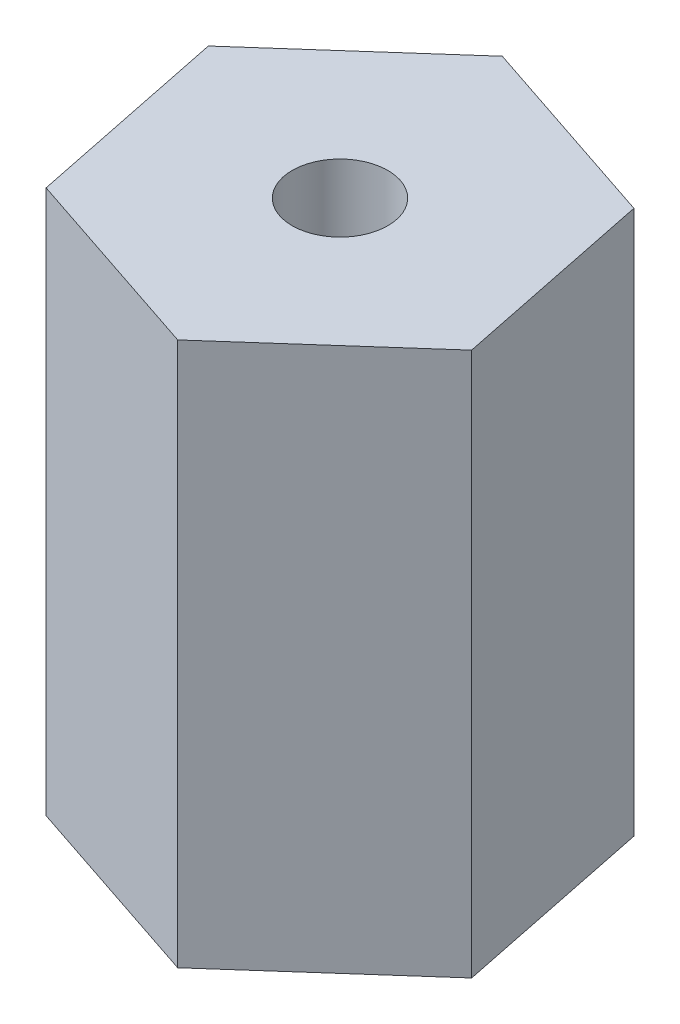
SolidWorks part; units mm, degrees
ref_plane "Front Plane" through (0, 0, 0) normal (0, 0, 1) x (1, 0, 0)
ref_plane "Top Plane" through (0, 0, 0) normal (0, 1, 0) x (1, 0, 0)
ref_plane "Right Plane" through (0, 0, 0) normal (1, 0, 0) x (0, 0, -1)
sketch "Sketch1" plane through (0, 0, 0) normal (0, 1, 0) x (1, 0, 0)
  line L1 (5.1581, 4.5716) -> (-1.3801, 6.7528)
  line L2 (-1.3801, 6.7528) -> (-6.5382, 2.1812)
  line L3 (-6.5382, 2.1812) -> (-5.1581, -4.5716)
  line L4 (-5.1581, -4.5716) -> (1.3801, -6.7528)
  line L5 (1.3801, -6.7528) -> (6.5382, -2.1812)
  line L6 (6.5382, -2.1812) -> (5.1581, 4.5716)
  circle A1 centre (0, 0) radius 5.969 construction
  dimension "D1" = 11.938
extrude "Boss-Extrude1" add sketch "Sketch1" along normal blind 18
sketch "Sketch2" plane through (0, 18, 0) normal (0, 1, 0) x (1, 0, 0)
  circle A0 centre (0, 0) radius 1.585
  dimension "D1" = 3.17
extrude "Cut-Extrude1" cut sketch "Sketch2" against normal through all
equation "\"MDF\"= 4.8mm"
equation "\"Foamcore\"= 4.6mm"
equation "\"PCB\" = 1.6mm"
equation "\"GMaterial\"= \"MDF\""
equation "\"BaseWidth\" = 10in"
equation "\"SkidLength\" = 1in"
equation "\"SkidClearance\" = 0.4in"
equation "\"MotorMountLength\" = 2in"
equation "\"MotorMountWidth\" = \"GMaterial\""
equation "\"MotorMountHeight\" = 2.25in"
equation "\"UnoStackWidth\" = 77.4mm"
equation "\"UnoStackLength\" = 79.8mm"
equation "\"UnoStackHeight\" = 34.2mm"
equation "\"TallHexRiserHeight\" = 22.2mm"
equation "\"PingPongBallSize\" = 40mm"
equation "\"BarrelLength\" = 9in"
equation "\"BarrelSize\" = \"PingPongBallSize\""
equation "\"PlatformLength\" = 4in"
equation "\"PlatformWidth\" = 6in"
equation "\"WheelWidth\"= 26mm"
equation "\"WheelDiameter\"=2.99213"
equation "\"ServoMountHeight\"=2.49223"
equation "\"ServoGearHeight\" = 0.95330261in"
equation "\"ServoMountLength\"= 1.53774"
equation "\"PivotHoleRadius\"= 0.616358"
equation "\"PlatformMountHeight\" = 3.19"
equation "\"TensionOffSet\"= .3mm"
equation "\"MotorMountWedge\"=0.333333"
equation "\"LaserCutterOffset\"= .3mm"
equation "\"BumperWidth\"=11"
equation "\"PitchingWheelBoltShoulder\" = 4.5mm"
equation "\"BrassCouplingLength\" = 18mm"
equation "\"PitcherWheelCompression\" = 2.5mm"
equation "\"PitchingMotorHeight\" = 57.0mm"
equation "\"PitchingMotorShaftTopHeight\" = \"PitchingMotorHeight\" - 44.1mm"
equation "\"PitchingMotorBodyHeight\" = 38mm"
equation "\"PitchingMotorTopShoulderHeight\" = 40.6mm - \"PitchingMotorBodyHeight\" "
equation "\"PitchingMotorBottomShoulderHeight\" = 40.2mm - \"PitchingMotorBodyHeight\""
equation "\"PitchingMotorBottomShaftHeight\" = \"PitchingMotorHeight\" - \"PitchingMotorShaftTopHeight\" - \"PitchingMotorTopShoulderHeight\" - \"PitchingMotorBodyHeight\" - \"PitchingMotorBottomShoulderHeight\""
equation "\"PitchingMotorShaftDiameter\" = 2.2mm"
equation "\"PitchingMotorBodyDiameter\" = 27.4mm"
equation "\"PitchingMotorTopShoulderDiameter\" = 9.8mm"
equation "\"PitchingMotorBottomShoulderDiameter\" = 9.8mm"
equation "\"BrassCouplingHexSize\" = 12mm"
equation "\"BrassCouplingBoreSize\" = 3.17mm"
equation "\"D1@Boss-Extrude1\"=\"BrassCouplingLength\""
equation "\"D1@Sketch2\"=\"BrassCouplingBoreSize\""
